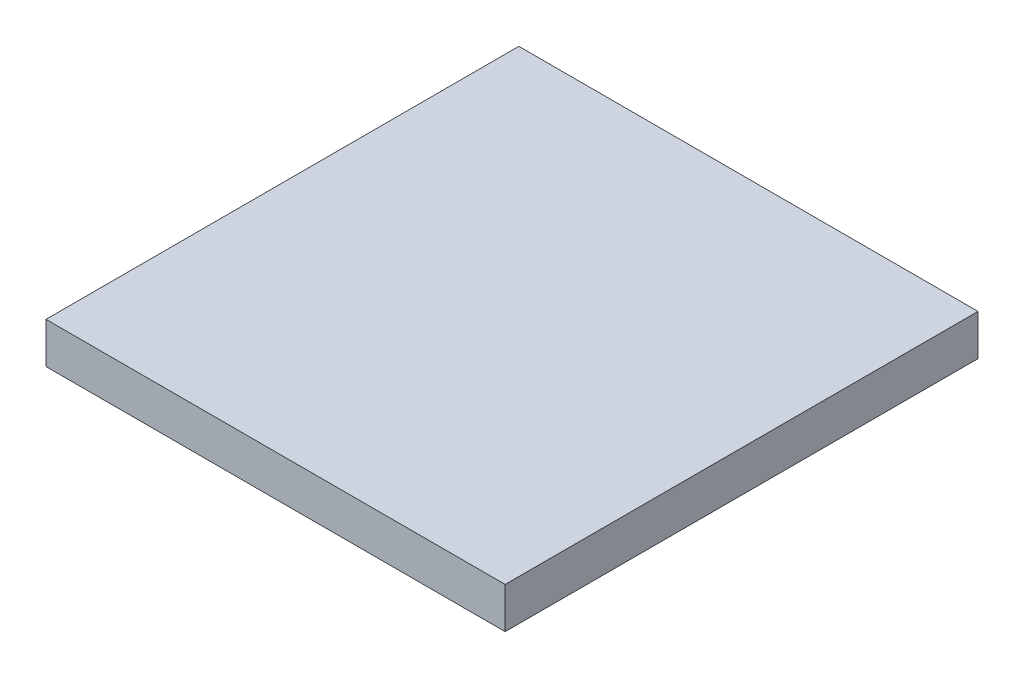
SolidWorks part; units mm, degrees
ref_plane "Front Plane" through (0, 0, 0) normal (0, 0, 1) x (1, 0, 0)
ref_plane "Top Plane" through (0, 0, 0) normal (0, 1, 0) x (1, 0, 0)
ref_plane "Right Plane" through (0, 0, 0) normal (1, 0, 0) x (0, 0, -1)
sketch "Sketch1" plane through (0, 0, 0) normal (0, 1, 0) x (1, 0, 0)
  line L1 (-44.942, 44.2127) -> (40.5663, 44.2127)
  line L2 (-44.942, 44.2127) -> (-44.942, -43.8481)
  line L3 (-44.942, -43.8481) -> (40.5663, -43.8481)
  line L4 (40.5663, 44.2127) -> (40.5663, -43.8481)
extrude "Boss-Extrude1" add sketch "Sketch1" along normal blind 7.62 contours L4 L3 L2 L1
